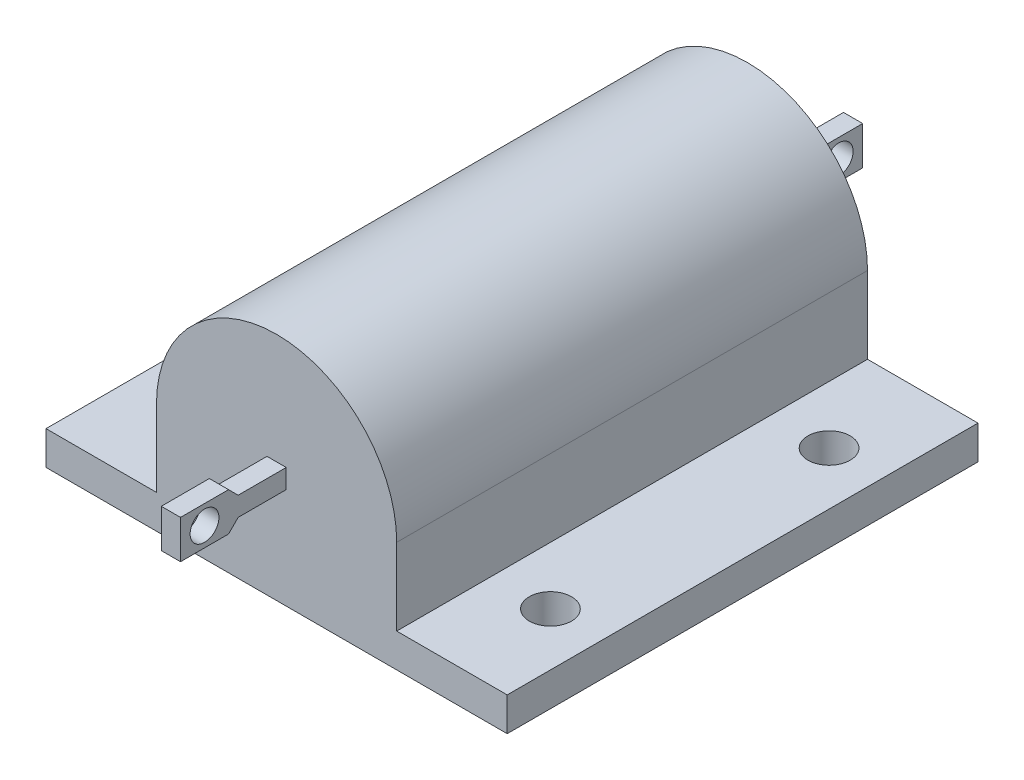
SolidWorks part; units mm, degrees
ref_plane "Front Plane" through (0, 0, 0) normal (0, 0, 1) x (1, 0, 0)
ref_plane "Top Plane" through (0, 0, 0) normal (0, 1, 0) x (1, 0, 0)
ref_plane "Right Plane" through (0, 0, 0) normal (1, 0, 0) x (0, 0, -1)
sketch "Sketch1" plane through (0, 0, 0) normal (0, 0, 1) x (1, 0, 0)
  line L0 (12.5, -8) -> (24, -8)
  line L1 (-24, -11.5) -> (24, -11.5)
  line L2 (-24, -11.5) -> (-24, -8)
  line L3 (-24, -8) -> (-12.5, -8)
  line L4 (24, -11.5) -> (24, -8)
  line L5 (-12.5, 0) -> (-12.5, -8)
  line L6 (12.5, 0) -> (12.5, -8)
  arc A0 (12.5, 0) -> (-12.5, 0) centre (0, 0) ccw
  point P12 (-12.5, -8)
  dimension "D1" = 24
  dimension "D2" = 3.5
  dimension "D3" = 11.5
  dimension "D4" = 48
extrude "Boss-Extrude1" add sketch "Sketch1" along normal mid plane 49
sketch "Sketch2" plane through (0, -8, 0) normal (0, 1, 0) x (1, 0, 0)
  line L1 (18.5, -14.5) -> (-18.5, -14.5) construction
  line L2 (18.5, -14.5) -> (18.5, 14.5) construction
  line L3 (18.5, 14.5) -> (-18.5, 14.5) construction
  line L4 (-18.5, -14.5) -> (-18.5, 14.5) construction
  line L5 (18.5, -14.5) -> (-18.5, 14.5) construction
  line L6 (18.5, 14.5) -> (-18.5, -14.5) construction
  circle A0 centre (-18.5, 14.5) radius 2.2
  circle A1 centre (-18.5, -14.5) radius 2.2
  circle A2 centre (18.5, -14.5) radius 2.2
  circle A3 centre (18.5, 14.5) radius 2.2
  point P0 (0, 0)
  dimension "D1" = 4.4
  dimension "D2" = 29
  dimension "D3" = 37
extrude "Cut-Extrude1" cut sketch "Sketch2" against normal through all
sketch "Sketch3" plane through (0, 0, 0) normal (1, 0, 0) x (0, 0, -1)
  line L0 (-24.5, 1) -> (-29.5, 1)
  line L1 (-24.5, 12.5) -> (-24.5, 0) construction
  line L2 (-29.5, 1) -> (-30.5, 2)
  line L3 (-30.5, 2) -> (-35.5, 2)
  line L4 (-35.5, 2) -> (-35.5, -2)
  line L5 (-35.5, -2) -> (-30.5, -2)
  line L6 (-30.5, -2) -> (-29.5, -1)
  line L7 (-29.5, -1) -> (-24.5, -1)
  line L8 (-24.5, -8) -> (-24.5, 0) construction
  line L9 (-24.5, -1) -> (-24.5, 1)
  line L10 (0, 0) -> (0, -11.5) construction
  line L11 (-24.5, -11.5) -> (24.5, -11.5) construction
  line L12 (29.5, -1) -> (24.5, -1)
  line L13 (30.5, -2) -> (29.5, -1)
  line L14 (35.5, -2) -> (30.5, -2)
  line L15 (35.5, 2) -> (35.5, -2)
  line L16 (30.5, 2) -> (35.5, 2)
  line L17 (29.5, 1) -> (30.5, 2)
  line L18 (24.5, 1) -> (29.5, 1)
  line L19 (24.5, -1) -> (24.5, 1)
  line L20 (-33, 0) -> (-24.5, 0) construction
  line L21 (29.5, -1) -> (24.5, -1)
  line L22 (30.5, -2) -> (29.5, -1)
  line L23 (35.5, -2) -> (30.5, -2)
  line L24 (35.5, 2) -> (35.5, -2)
  line L25 (30.5, 2) -> (35.5, 2)
  line L26 (29.5, 1) -> (30.5, 2)
  line L27 (24.5, 1) -> (29.5, 1)
  line L28 (24.5, -1) -> (24.5, 1)
  circle A0 centre (-33, 0) radius 1.5
  circle A1 centre (33, 0) radius 1.5
  point P5 (-35.5, 0)
  point P26 (-30.7466, 1.0484)
  point P29 (-32.0089, 0)
  dimension "D1" = 4
  dimension "D5" = 3
  dimension "D2" = 5
  dimension "D3" = 45
  dimension "D4" = 1
  dimension "D6" = 71
  dimension "D7" = 2
extrude "Boss-Extrude2" add sketch "Sketch3" along normal mid plane 2 contours L7 L9 L0 L2 L3 L4 L5 L6 A0 | L19 L12 L13 L14 L15 L16 L17 L18 A1
